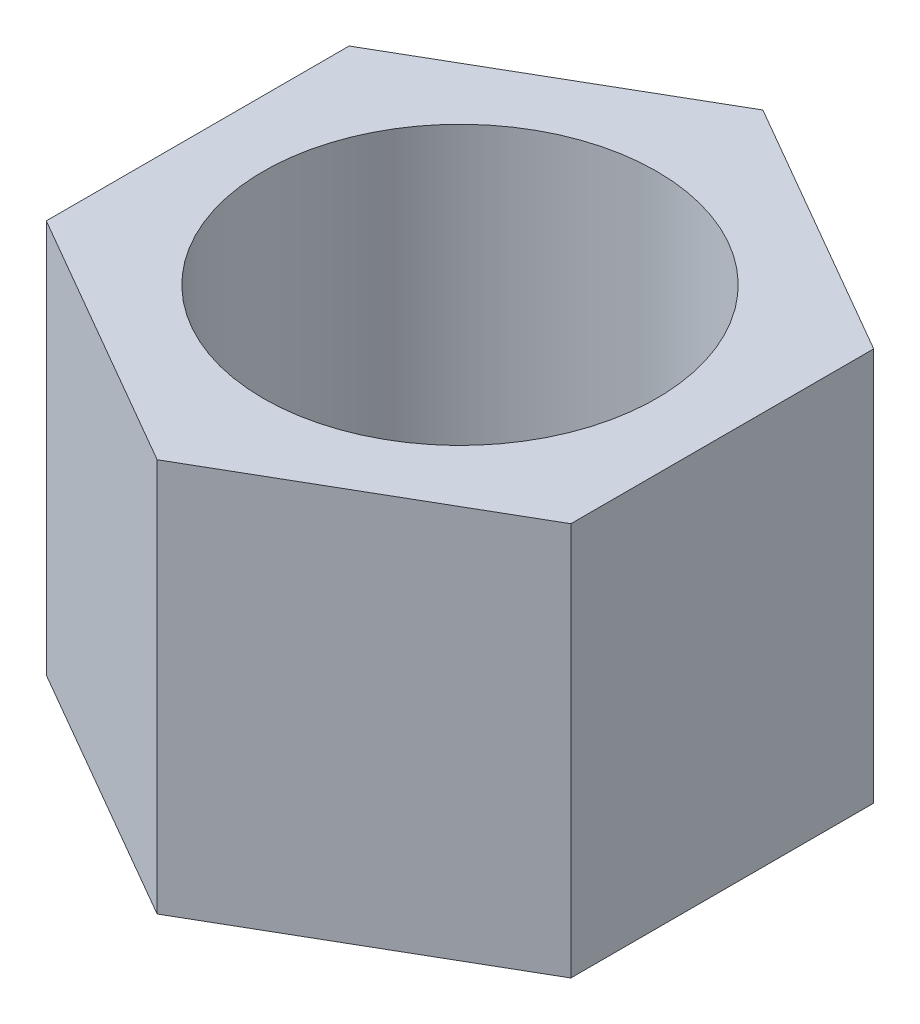
SolidWorks part; units mm, degrees
material "ABS"
ref_plane "前视基准面" through (0, 0, 0) normal (0, 0, 1) x (1, 0, 0)
ref_plane "上视基准面" through (0, 0, 0) normal (0, 1, 0) x (1, 0, 0)
ref_plane "右视基准面" through (0, 0, 0) normal (1, 0, 0) x (0, 0, -1)
sketch "草图1" plane through (0, 0, 0) normal (0, 1, 0) x (1, 0, 0)
  line L1 (0, 2.3094) -> (-2, 1.1547)
  line L2 (-2, 1.1547) -> (-2, -1.1547)
  line L3 (-2, -1.1547) -> (0, -2.3094)
  line L4 (0, -2.3094) -> (2, -1.1547)
  line L5 (2, -1.1547) -> (2, 1.1547)
  line L6 (2, 1.1547) -> (0, 2.3094)
  circle A0 centre (0, 0) radius 1.5
  circle A1 centre (0, 0) radius 2 construction
  dimension "D1" = 3
  dimension "D2" = 4
extrude "凸台-拉伸1" add sketch "草图1" along normal blind 3
